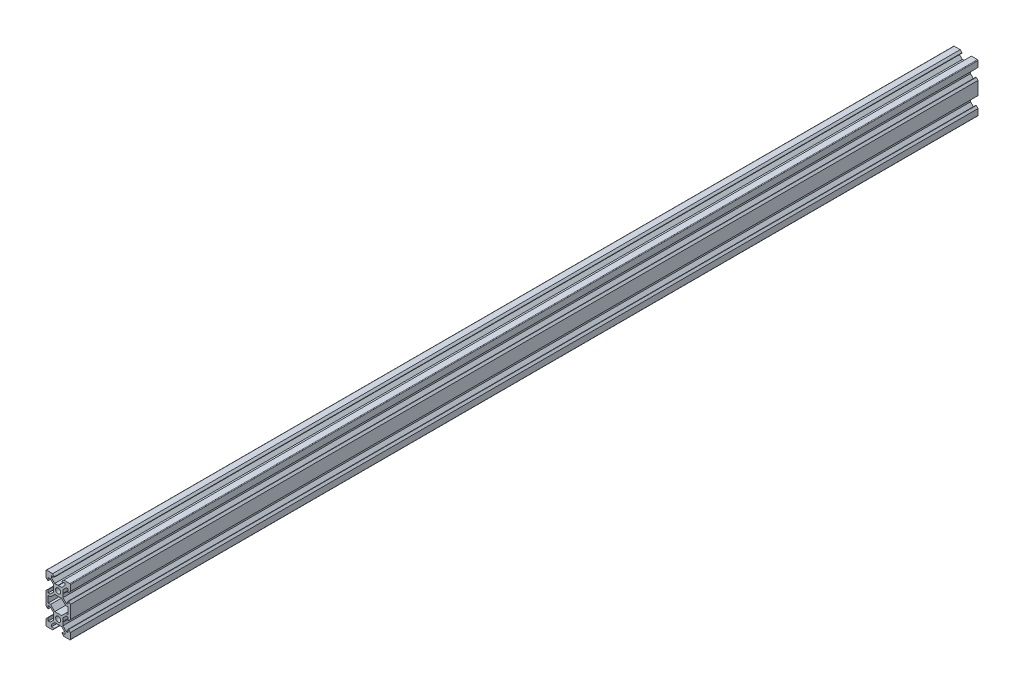
SolidWorks part; units mm, degrees
ref_plane "Front Plane" through (0, 0, 0) normal (0, 0, 1) x (1, 0, 0)
ref_plane "Top Plane" through (0, 0, 0) normal (0, 1, 0) x (1, 0, 0)
ref_plane "Right Plane" through (0, 0, 0) normal (1, 0, 0) x (0, 0, -1)
sketch "Sketch2" plane through (0, 0, 0) normal (0, 0, 1) x (1, 0, 0)
  line L106 (-6.1325, -2.3442) -> (-2.7325, -5.7442)
  line L107 (-8.0932, -2.3442) -> (-6.1325, -2.3442)
  line L108 (-8.0932, -2.3442) -> (-8.0932, 3.0558)
  line L109 (-8.0932, 3.0558) -> (-6.1325, 3.0558)
  line L110 (-6.1325, 3.0558) -> (-2.7325, 6.4558)
  line L111 (-2.7325, 6.4558) -> (2.9461, 6.4558)
  line L112 (6.3461, 3.0558) -> (2.9461, 6.4558)
  line L113 (8.3068, 3.0558) -> (6.3461, 3.0558)
  line L114 (8.3068, -2.3442) -> (8.3068, 3.0558)
  line L115 (8.3068, -2.3442) -> (6.3461, -2.3442)
  line L116 (6.3461, -2.3442) -> (2.9461, -5.7442)
  line L117 (-2.7325, -5.7442) -> (2.9461, -5.7442)
  line L118 (4.0068, 10.1458) -> (3.7968, 10.3558)
  line L119 (3.7968, 10.3558) -> (4.0068, 10.5658)
  line L120 (4.0068, 10.5658) -> (4.0068, 13.1951)
  line L121 (4.0068, 13.1951) -> (6.6675, 15.8558)
  line L122 (6.6675, 15.8558) -> (8.3068, 15.8558)
  line L123 (8.3068, 15.8558) -> (8.3068, 13.4808)
  line L124 (8.3068, 13.4808) -> (8.6518, 13.4808)
  line L125 (8.6518, 13.4808) -> (10.1068, 14.9358)
  line L126 (10.1068, 14.9358) -> (10.1068, 19.8558)
  line L127 (9.6068, 20.3558) -> (4.6868, 20.3558)
  line L128 (4.6868, 20.3558) -> (3.2318, 18.9008)
  line L129 (3.2318, 18.9008) -> (3.2318, 18.5558)
  line L130 (3.2318, 18.5558) -> (5.6068, 18.5558)
  line L131 (5.6068, 18.5558) -> (5.6068, 16.9165)
  line L132 (5.6068, 16.9165) -> (2.9461, 14.2558)
  line L133 (2.9461, 14.2558) -> (0.3168, 14.2558)
  line L134 (0.3168, 14.2558) -> (0.1068, 14.0458)
  line L135 (0.1068, 14.0458) -> (-0.1032, 14.2558)
  line L136 (-0.1032, 14.2558) -> (-2.7325, 14.2558)
  line L137 (-2.7325, 14.2558) -> (-5.3932, 16.9165)
  line L138 (-5.3932, 16.9165) -> (-5.3932, 18.5558)
  line L139 (-5.3932, 18.5558) -> (-3.0182, 18.5558)
  line L140 (-3.0182, 18.5558) -> (-3.0182, 18.9008)
  line L141 (-3.0182, 18.9008) -> (-4.4732, 20.3558)
  line L142 (-4.4732, 20.3558) -> (-9.3932, 20.3558)
  line L143 (-9.8932, 19.8558) -> (-9.8932, 14.9358)
  line L144 (-9.8932, 14.9358) -> (-8.4382, 13.4808)
  line L145 (-8.4382, 13.4808) -> (-8.0932, 13.4808)
  line L146 (-8.0932, 13.4808) -> (-8.0932, 15.8558)
  line L147 (-8.0932, 15.8558) -> (-6.4539, 15.8558)
  line L148 (-6.4539, 15.8558) -> (-3.7932, 13.1951)
  line L149 (-3.7932, 13.1951) -> (-3.7932, 10.5658)
  line L150 (-3.7932, 10.5658) -> (-3.5832, 10.3558)
  line L151 (-3.5832, 10.3558) -> (-3.7932, 10.1458)
  line L152 (-3.7932, 10.1458) -> (-3.7932, 7.5165)
  line L153 (-3.7932, 7.5165) -> (-6.4539, 4.8558)
  line L154 (-6.4539, 4.8558) -> (-8.0932, 4.8558)
  line L155 (-8.0932, 4.8558) -> (-8.0932, 7.2308)
  line L156 (-8.0932, 7.2308) -> (-8.4382, 7.2308)
  line L157 (-8.4382, 7.2308) -> (-9.8932, 5.7758)
  line L158 (-9.8932, 5.7758) -> (-9.8932, -5.0642)
  line L159 (-9.8932, -5.0642) -> (-8.4382, -6.5192)
  line L160 (-8.4382, -6.5192) -> (-8.0932, -6.5192)
  line L161 (-8.0932, -6.5192) -> (-8.0932, -4.1442)
  line L162 (-8.0932, -4.1442) -> (-6.4539, -4.1442)
  line L163 (-6.4539, -4.1442) -> (-3.7932, -6.8049)
  line L164 (-3.7932, -6.8049) -> (-3.7932, -9.4342)
  line L165 (-3.7932, -9.4342) -> (-3.5832, -9.6442)
  line L166 (-3.5832, -9.6442) -> (-3.7932, -9.8542)
  line L167 (-3.7932, -9.8542) -> (-3.7932, -12.4835)
  line L168 (-3.7932, -12.4835) -> (-6.4539, -15.1442)
  line L169 (-6.4539, -15.1442) -> (-8.0932, -15.1442)
  line L170 (-8.0932, -15.1442) -> (-8.0932, -12.7692)
  line L171 (-8.0932, -12.7692) -> (-8.4382, -12.7692)
  line L172 (-8.4382, -12.7692) -> (-9.8932, -14.2242)
  line L173 (-9.8932, -14.2242) -> (-9.8932, -19.1442)
  line L174 (-9.3932, -19.6442) -> (-4.4732, -19.6442)
  line L175 (-4.4732, -19.6442) -> (-3.0182, -18.1892)
  line L176 (-3.0182, -18.1892) -> (-3.0182, -17.8442)
  line L177 (-3.0182, -17.8442) -> (-5.3932, -17.8442)
  line L178 (-5.3932, -17.8442) -> (-5.3932, -16.2049)
  line L179 (-5.3932, -16.2049) -> (-2.7325, -13.5442)
  line L180 (-2.7325, -13.5442) -> (-0.1032, -13.5442)
  line L181 (-0.1032, -13.5442) -> (0.1068, -13.3342)
  line L182 (0.1068, -13.3342) -> (0.3168, -13.5442)
  line L183 (0.3168, -13.5442) -> (2.9461, -13.5442)
  line L184 (2.9461, -13.5442) -> (5.6068, -16.2049)
  line L185 (5.6068, -16.2049) -> (5.6068, -17.8442)
  line L186 (5.6068, -17.8442) -> (3.2318, -17.8442)
  line L187 (3.2318, -17.8442) -> (3.2318, -18.1892)
  line L188 (3.2318, -18.1892) -> (4.6868, -19.6442)
  line L189 (4.6868, -19.6442) -> (9.6068, -19.6442)
  line L190 (10.1068, -19.1442) -> (10.1068, -14.2242)
  line L191 (10.1068, -14.2242) -> (8.6518, -12.7692)
  line L192 (8.6518, -12.7692) -> (8.3068, -12.7692)
  line L193 (8.3068, -12.7692) -> (8.3068, -15.1442)
  line L194 (8.3068, -15.1442) -> (6.6675, -15.1442)
  line L195 (6.6675, -15.1442) -> (4.0068, -12.4835)
  line L196 (4.0068, -12.4835) -> (4.0068, -9.8542)
  line L197 (4.0068, -9.8542) -> (3.7968, -9.6442)
  line L198 (3.7968, -9.6442) -> (4.0068, -9.4342)
  line L199 (4.0068, -9.4342) -> (4.0068, -6.8049)
  line L200 (4.0068, -6.8049) -> (6.6675, -4.1442)
  line L201 (6.6675, -4.1442) -> (8.3068, -4.1442)
  line L202 (8.3068, -4.1442) -> (8.3068, -6.5192)
  line L203 (8.3068, -6.5192) -> (8.6518, -6.5192)
  line L204 (8.6518, -6.5192) -> (10.1068, -5.0642)
  line L205 (10.1068, -5.0642) -> (10.1068, 5.7758)
  line L206 (10.1068, 5.7758) -> (8.6518, 7.2308)
  line L207 (8.6518, 7.2308) -> (8.3068, 7.2308)
  line L208 (8.3068, 7.2308) -> (8.3068, 4.8558)
  line L209 (8.3068, 4.8558) -> (6.6675, 4.8558)
  line L210 (6.6675, 4.8558) -> (4.0068, 7.5165)
  line L211 (4.0068, 7.5165) -> (4.0068, 10.1458)
  circle A4 centre (0.1068, -9.6442) radius 2.1
  circle A5 centre (0.1068, 10.3558) radius 2.1
  arc A6 (10.1068, 19.8558) -> (9.6068, 20.3558) centre (9.6068, 19.8558) ccw
  arc A7 (-9.3932, 20.3558) -> (-9.8932, 19.8558) centre (-9.3932, 19.8558) ccw
  arc A8 (-9.8932, -19.1442) -> (-9.3932, -19.6442) centre (-9.3932, -19.1442) ccw
  arc A9 (9.6068, -19.6442) -> (10.1068, -19.1442) centre (9.6068, -19.1442) ccw
extrude "Boss-Extrude1" add sketch "Sketch2" along normal blind 745
